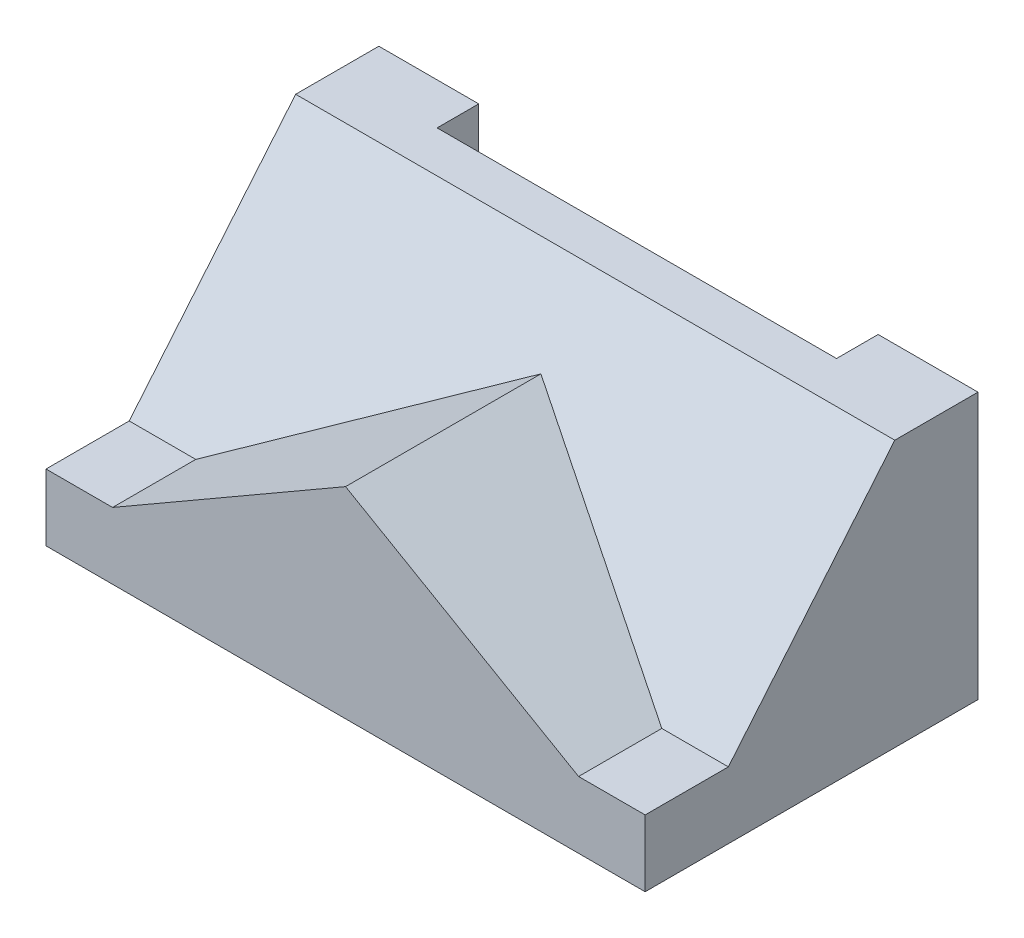
SolidWorks part; units mm, degrees
ref_plane "前基準面" through (0, 0, 0) normal (0, 0, 1) x (1, 0, 0)
ref_plane "上基準面" through (0, 0, 0) normal (0, 1, 0) x (1, 0, 0)
ref_plane "右基準面" through (0, 0, 0) normal (1, 0, 0) x (0, 0, -1)
sketch "草圖1" plane through (0, 0, 0) normal (1, 0, 0) x (0, 0, -1)
  line L0 (0, 0) -> (40, 0)
  line L1 (40, 0) -> (40, 32)
  line L2 (40, 32) -> (30, 32)
  line L3 (0, 8) -> (10, 8)
  line L4 (0, 8) -> (0, 0)
  line L5 (10, 8) -> (30, 32)
  dimension "D1" = 8
  dimension "D2" = 32
  dimension "D3" = 10
  dimension "D4" = 40
  dimension "D5" = 10
extrude "伸長1" add sketch "草圖1" along normal mid plane 72
sketch "草圖2" plane through (0, 0, 0) normal (0, 0, 1) x (1, 0, 0)
  line L0 (36, 8) -> (-36, 8) construction
  line L1 (28, 8) -> (-28, 8)
  line L2 (0, 0) -> (0, 29.9598) construction
  line L3 (0, 24.1658) -> (-28, 8)
  line L4 (0, 24.1658) -> (28, 8)
  line L5 (-36, 8) -> (-36, 0) construction
  dimension "D1" = 120
  dimension "D2" = 8
extrude "伸長2" add sketch "草圖2" against normal up to next
sketch "草圖3" plane through (0, 32, 0) normal (0, 1, 0) x (1, 0, 0)
  line L0 (36, 40) -> (-36, 40) construction
  line L1 (-24, 40) -> (24, 40)
  line L2 (-24, 40) -> (-24, 35)
  line L3 (-24, 35) -> (24, 35)
  line L4 (24, 40) -> (24, 35)
  line L5 (0, 0) -> (0, 35) construction
  dimension "D1" = 48
  dimension "D2" = 5
extrude "伸長3" cut sketch "草圖3" against normal through all
